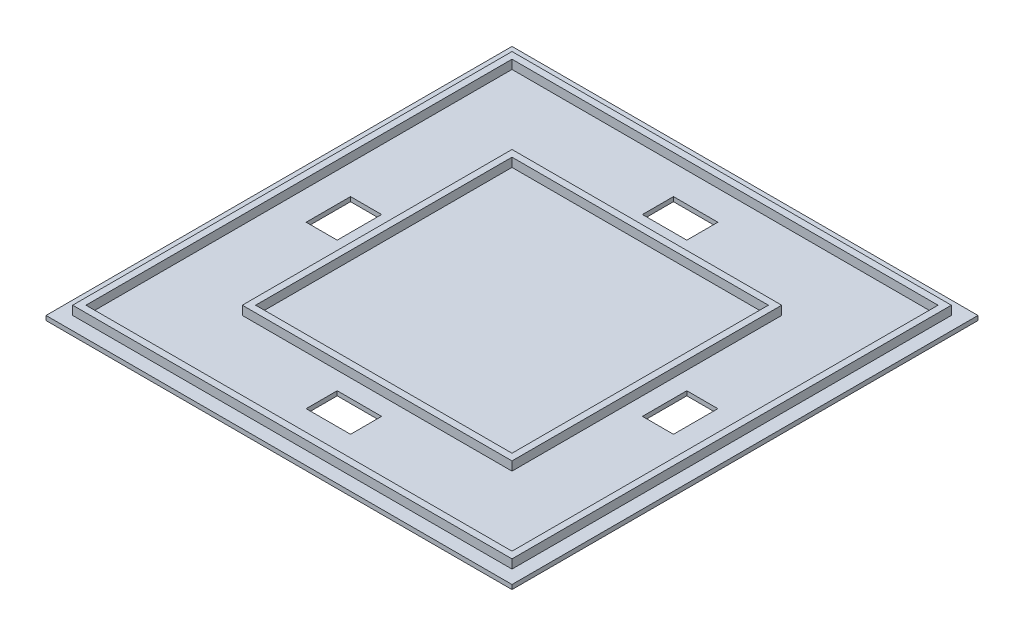
SolidWorks part; units mm, degrees
ref_plane "Alzado" through (0, 0, 0) normal (0, 0, 1) x (1, 0, 0)
ref_plane "Planta" through (0, 0, 0) normal (0, 1, 0) x (1, 0, 0)
ref_plane "Vista lateral" through (0, 0, 0) normal (1, 0, 0) x (0, 0, -1)
sketch "Croquis1" plane through (0, 0, 0) normal (0, 1, 0) x (1, 0, 0)
  line L0 (1.5, 1.5) -> (1.5, 97.5)
  line L1 (0, 0) -> (99, 0)
  line L2 (0, 0) -> (0, 99)
  line L3 (0, 99) -> (99, 99)
  line L4 (99, 0) -> (99, 99)
  line L5 (1.5, 97.5) -> (97.5, 97.5)
  line L6 (97.5, 1.5) -> (97.5, 97.5)
  line L7 (1.5, 1.5) -> (97.5, 1.5)
  dimension "D1" = 99
  dimension "D2" = 1.5
extrude "Saliente-Extruir1" add sketch "Croquis1" along normal blind 2
sketch "Croquis2" plane through (0, 0, 0) normal (0, -1, 0) x (1, 0, 0)
  line L0 (1.5, -97.5) -> (1.5, -1.5) construction
  line L1 (1.5, -44.5) -> (97.5, -44.5)
  line L2 (1.5, -44.5) -> (1.5, -54.5)
  line L3 (1.5, -49.5) -> (97.5, -49.5)
  line L4 (97.5, -44.5) -> (97.5, -54.5)
  line L5 (97.5, -1.5) -> (97.5, -97.5) construction
  line L6 (49.5, -10.1) -> (49.5, -1.5) construction
  line L7 (1.5, -35.9) -> (97.5, -35.9)
  line L8 (1.5, -35.9) -> (1.5, -27.3)
  line L9 (1.5, -27.3) -> (97.5, -27.3)
  line L10 (97.5, -35.9) -> (97.5, -27.3)
  line L11 (1.5, -18.7) -> (97.5, -18.7)
  line L12 (1.5, -18.7) -> (1.5, -10.1)
  line L13 (1.5, -10.1) -> (97.5, -10.1)
  line L14 (97.5, -18.7) -> (97.5, -10.1)
  line L15 (1.5, -1.5) -> (97.5, -1.5) construction
  line L16 (49.5, -10.1) -> (49.5, -18.7) construction
  line L17 (49.5, -18.7) -> (49.5, -27.3) construction
  line L18 (49.5, -27.3) -> (49.5, -35.9) construction
  line L19 (49.5, -35.9) -> (49.5, -44.5) construction
  line L20 (49.5, -44.5) -> (49.5, -49.5) construction
  line L21 (1.5, -54.5) -> (97.5, -54.5)
  line L22 (1.5, -71.7) -> (97.5, -71.7)
  line L23 (97.5, -63.1) -> (97.5, -71.7)
  line L24 (1.5, -63.1) -> (97.5, -63.1)
  line L25 (1.5, -63.1) -> (1.5, -71.7)
  line L26 (1.5, -88.9) -> (97.5, -88.9)
  line L27 (97.5, -80.3) -> (97.5, -88.9)
  line L28 (1.5, -80.3) -> (97.5, -80.3)
  line L29 (1.5, -80.3) -> (1.5, -88.9)
  point P16 (1.5, -49.5)
  line M23 (1.5, -97.5) -> (1.5, -1.5)
  line M25 (97.5, -1.5) -> (97.5, -97.5)
  dimension "D1" = 5
extrude "Saliente-Extruir2" add sketch "Croquis2" against normal blind 1 contours L21 L3 M23 M25 | L2 L3 L1 M25 | L24 L22 M23 M25 | L28 L26 M23 M25 | L9 L7 M23 M25 | L13 L11 M23 M25
sketch "Croquis3" plane through (0, 0, 0) normal (0, -1, 0) x (1, 0, 0)
  line L0 (99, -99) -> (0, -99) construction
  line L1 (99, 0) -> (99, -99) construction
  line L2 (0, -99) -> (0, 0) construction
  line L3 (0, 0) -> (99, 0) construction
  line L4 (99, -99) -> (0, -99)
  line L5 (99, 0) -> (99, -99)
  line L6 (0, -99) -> (0, 0)
  line L7 (0, 0) -> (99, 0)
  line L8 (-3, -102) -> (-3, 3)
  line L9 (-3, 3) -> (102, 3)
  line L10 (102, 3) -> (102, -102)
  line L11 (102, -102) -> (-3, -102)
  dimension "D1" = 3
extrude "Saliente-Extruir3" add sketch "Croquis3" against normal blind 1
sketch "Croquis6" plane through (0, 1, 0) normal (0, 1, 0) x (1, 0, 0)
  line L1 (1.5, 97.5) -> (97.5, 97.5)
  line L2 (1.5, 97.5) -> (1.5, 1.5)
  line L3 (1.5, 1.5) -> (97.5, 1.5)
  line L4 (97.5, 97.5) -> (97.5, 1.5)
extrude "Saliente-Extruir5" add sketch "Croquis6" against normal up to surface (1 mm away) up to face at (49.5, 0, -23)
sketch "Croquis7" plane through (0, 1, 0) normal (0, 1, 0) x (1, 0, 0)
  line L0 (49.5, 78.3846) -> (49.5, 97.5) construction
  line L1 (20.6154, 20.6154) -> (78.3846, 20.6154)
  line L2 (20.6154, 20.6154) -> (20.6154, 78.3846)
  line L3 (20.6154, 78.3846) -> (78.3846, 78.3846)
  line L4 (78.3846, 20.6154) -> (78.3846, 78.3846)
  line L5 (97.5, 97.5) -> (1.5, 97.5) construction
  line L6 (78.3846, 49.5) -> (97.5, 49.5) construction
  line L7 (97.5, 1.5) -> (97.5, 97.5) construction
  line L8 (19.1154, 19.1154) -> (19.1154, 79.8846)
  line L9 (19.1154, 79.8846) -> (79.8846, 79.8846)
  line L10 (79.8846, 19.1154) -> (79.8846, 79.8846)
  line L11 (19.1154, 19.1154) -> (79.8846, 19.1154)
  dimension "D1" = 57.7692
  dimension "D2" = 1.5
extrude "Saliente-Extruir6" add sketch "Croquis7" along normal blind 2
sketch "Croquis8" plane through (0, 1, 0) normal (0, 1, 0) x (1, 0, 0)
  line L0 (20.6154, 78.3846) -> (78.3846, 20.6154) construction
  line L1 (44.5, 15.1154) -> (54.5, 15.1154)
  line L2 (44.5, 15.1154) -> (44.5, 8.1154)
  line L3 (44.5, 8.1154) -> (54.5, 8.1154)
  line L4 (54.5, 15.1154) -> (54.5, 8.1154)
  line L5 (49.5, 15.1154) -> (49.5, 19.1154) construction
  line L6 (19.1154, 19.1154) -> (79.8846, 19.1154) construction
  line L7 (19.1154, 19.1154) -> (79.8846, 19.1154) construction
  line L8 (15.1154, 54.5) -> (8.1154, 54.5)
  line L9 (15.1154, 54.5) -> (15.1154, 44.5)
  line L10 (15.1154, 44.5) -> (8.1154, 44.5)
  line L11 (8.1154, 54.5) -> (8.1154, 44.5)
  line L12 (54.5, 83.8846) -> (54.5, 90.8846)
  line L13 (54.5, 83.8846) -> (44.5, 83.8846)
  line L14 (44.5, 83.8846) -> (44.5, 90.8846)
  line L15 (54.5, 90.8846) -> (44.5, 90.8846)
  line L16 (83.8846, 44.5) -> (90.8846, 44.5)
  line L17 (83.8846, 44.5) -> (83.8846, 54.5)
  line L18 (83.8846, 54.5) -> (90.8846, 54.5)
  line L19 (90.8846, 44.5) -> (90.8846, 54.5)
  dimension "D1" = 10
  dimension "D2" = 7
  dimension "D3" = 4
  dimension "D4" = 4
extrude "Cortar-Extruir1" cut sketch "Croquis8" against normal blind 65
sketch "Croquis9" plane through (0, 2, 0) normal (0, 1, 0) x (1, 0, 0)
  line L0 (1.5, 1.5) -> (97.5, 1.5) construction
  line L1 (1.5, 97.5) -> (1.5, 1.5) construction
  line L2 (97.5, 97.5) -> (1.5, 97.5) construction
  line L3 (97.5, 1.5) -> (97.5, 97.5) construction
  line L4 (0, 99) -> (0, 0)
  line L5 (0, 0) -> (99, 0)
  line L6 (99, 0) -> (99, 99)
  line L7 (99, 99) -> (0, 99)
  line L8 (0, 99) -> (0, 0)
  line L9 (0, 0) -> (99, 0)
  line L10 (99, 0) -> (99, 99)
  line L11 (99, 99) -> (0, 99)
  line L12 (1.5, 1.5) -> (97.5, 1.5)
  line L13 (1.5, 97.5) -> (1.5, 1.5)
  line L14 (97.5, 97.5) -> (1.5, 97.5)
  line L15 (97.5, 1.5) -> (97.5, 97.5)
  dimension "D1" = 0
extrude "Saliente-Extruir7" add sketch "Croquis9" along normal blind 1
